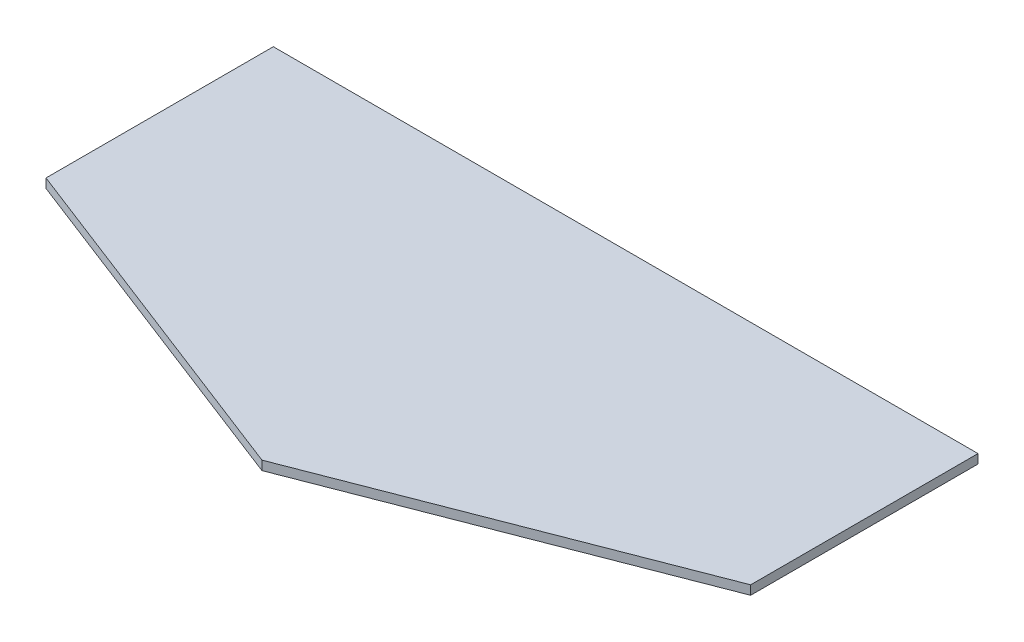
SolidWorks part; units mm, degrees
ref_plane "Front Plane" through (0, 0, 0) normal (0, 0, 1) x (1, 0, 0)
ref_plane "Top Plane" through (0, 0, 0) normal (0, 1, 0) x (1, 0, 0)
ref_plane "Right Plane" through (0, 0, 0) normal (1, 0, 0) x (0, 0, -1)
sketch "Sketch1" plane through (0, 0, 0) normal (0, 1, 0) x (1, 0, 0)
  line L0 (0, -100) -> (155, -160)
  line L1 (0, 0) -> (310, 0)
  line L2 (0, 0) -> (0, -100)
  line L3 (0, -100) -> (310, -100)
  line L4 (310, 0) -> (310, -100)
  line L5 (155, -160) -> (310, -100)
  line L6 (155, -160) -> (155, -100) construction
  dimension "D1" = 310
  dimension "D2" = 100
  dimension "D3" = 60
extrude "Boss-Extrude1" add sketch "Sketch1" along normal blind 4 contours L0 L6 L3 | L4 L1 L2 L3 | L6 L5 L3
scale "Scale1" bodies to scale 101 scale about centroid uniform scaling yes scale factor 0.5
ref_plane "Plane1" through (155, 0, 0) normal (1, 0, 0) x (0, 0, -1)
